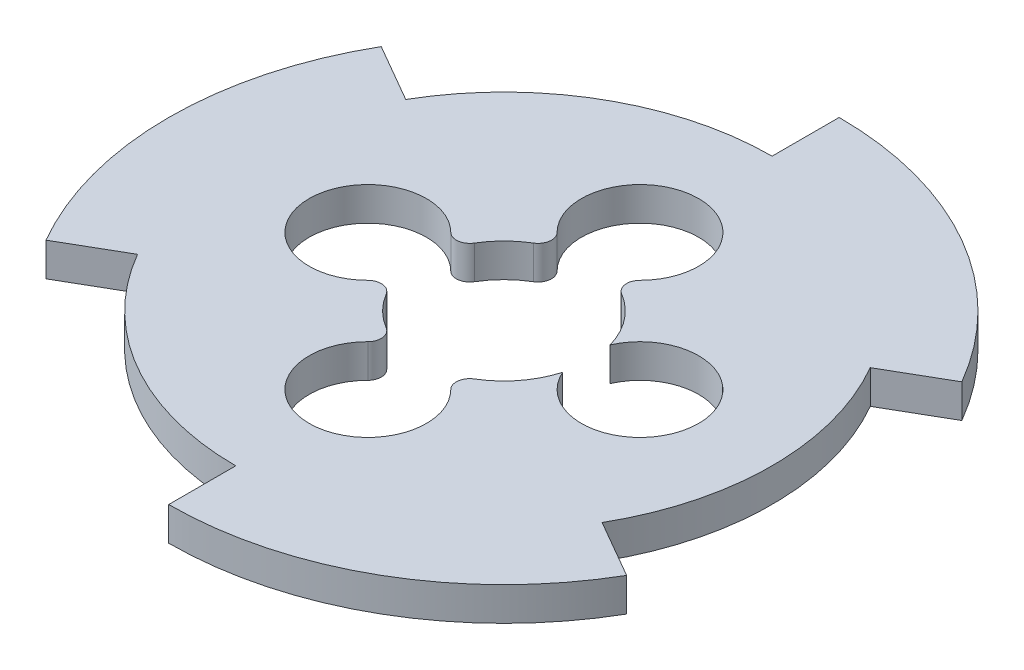
SolidWorks part; units mm, degrees
ref_plane "Front Plane" through (0, 0, 0) normal (0, 0, 1) x (1, 0, 0)
ref_plane "Top Plane" through (0, 0, 0) normal (0, 1, 0) x (1, 0, 0)
ref_plane "Right Plane" through (0, 0, 0) normal (1, 0, 0) x (0, 0, -1)
sketch "Sketch1" plane through (0, 0, 0) normal (0, 1, 0) x (1, 0, 0)
  line L0 (0, 50.8) -> (0, 63.5)
  line L1 (43.9941, -25.4) -> (54.9926, -31.75)
  line L2 (43.9941, 25.4) -> (54.9926, 31.75)
  line L3 (0, -50.8) -> (0, -63.5)
  line L4 (-43.9941, -25.4) -> (-54.9926, -31.75)
  line L5 (-43.9941, 25.4) -> (-54.9926, 31.75)
  arc A0 (-4.5005, 15.6206) -> (-15.6206, 4.5005) centre (0, 0) ccw
  arc A1 (-54.9926, 31.75) -> (-54.9926, -31.75) centre (0, 0) ccw
  arc A2 (4.5005, 15.6206) -> (-4.5005, 15.6206) centre (0, 25.781) ccw
  arc A3 (15.6206, -4.5005) -> (15.6206, 4.5005) centre (25.781, 0) ccw
  arc A4 (-4.5005, -15.6206) -> (4.5005, -15.6206) centre (0, -25.781) ccw
  arc A5 (-15.6206, 4.5005) -> (-15.6206, -4.5005) centre (-25.781, 0) ccw
  arc A6 (0, 50.8) -> (-43.9941, 25.4) centre (0, 0) ccw
  arc A7 (-43.9941, -25.4) -> (0, -50.8) centre (0, 0) ccw
  arc A8 (0, -63.5) -> (54.9926, -31.75) centre (0, 0) ccw
  arc A9 (43.9941, -25.4) -> (43.9941, 25.4) centre (0, 0) ccw
  arc A10 (54.9926, 31.75) -> (0, 63.5) centre (0, 0) ccw
  arc A11 (15.6206, 4.5005) -> (4.5005, 15.6206) centre (0, 0) ccw
  arc A12 (4.5005, -15.6206) -> (15.6206, -4.5005) centre (0, 0) ccw
  arc A13 (-15.6206, -4.5005) -> (-4.5005, -15.6206) centre (0, 0) ccw
  point P15 (0, 0)
  point P27 (0, 0)
  dimension "D1" = 32.512
  dimension "D2" = 22.225
  dimension "D3" = 25.781
  dimension "D5" = 3
  dimension "D4" = 4
extrude "Boss-Extrude1" add sketch "Sketch1" along normal blind 6.35
fillet "Fillet1" radius 2.54 6 edges at (-15.6206, 3.175, 4.5005) (-4.5005, 3.175, 15.6206) (4.5005, 3.175, 15.6206) (4.5005, 3.175, -15.6206) (-4.5005, 3.175, -15.6206) (-15.6206, 3.175, -4.5005)
